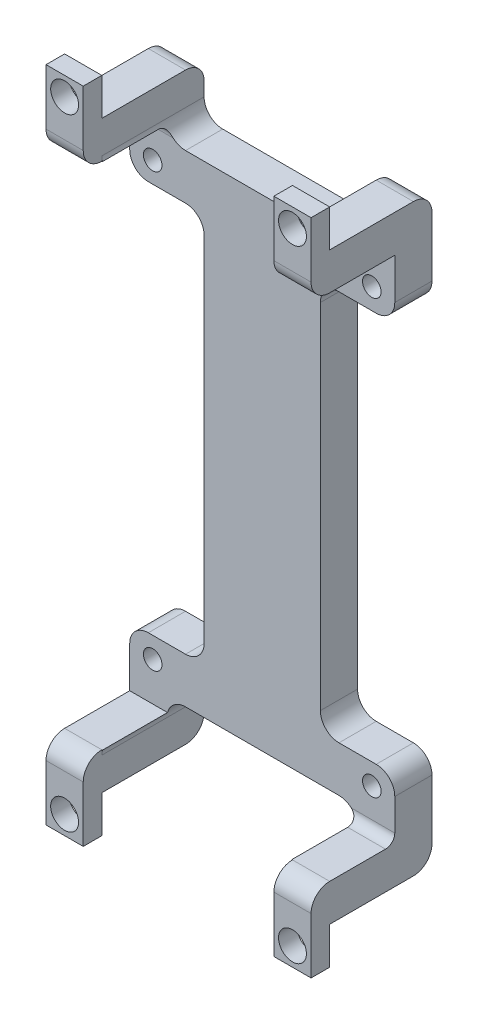
SolidWorks part; units mm, degrees
ref_plane "Front Plane" through (0, 0, 0) normal (0, 0, 1) x (1, 0, 0)
ref_plane "Top Plane" through (0, 0, 0) normal (0, 1, 0) x (1, 0, 0)
ref_plane "Right Plane" through (0, 0, 0) normal (1, 0, 0) x (0, 0, -1)
sketch "Sketch3" plane through (0, 0, 0) normal (0, 0, 1) x (-1, 0, 0)
  line L6 (-14.25, -25.9) -> (14.25, -25.9)
  line L7 (-14.25, -25.9) -> (-14.25, 25.9)
  line L8 (-14.25, 25.9) -> (14.25, 25.9)
  line L9 (14.25, -25.9) -> (14.25, 25.9)
  line L10 (-14.25, -25.9) -> (14.25, 25.9) construction
  line L11 (-14.25, 25.9) -> (14.25, -25.9) construction
  point P0 (0, 0)
  dimension "D1" = 51.8
  dimension "D2" = 28.5
extrude "Boss-Extrude4" add sketch "Sketch3" along normal blind 4
sketch "Sketch7" plane through (0, 25.9, 0) normal (0, 1, 0) x (1, 0, 0)
  line L1 (-14.25, -4) -> (-10.25, -4)
  line L2 (-14.25, -4) -> (-14.25, 0)
  line L3 (-14.25, 0) -> (-10.25, 0)
  line L4 (-10.25, -4) -> (-10.25, 0)
  line L5 (14.25, 0) -> (-14.25, 0) construction
  line L7 (14.25, -4) -> (10.25, -4)
  line L8 (14.25, -4) -> (14.25, 0)
  line L9 (14.25, 0) -> (10.25, 0)
  line L10 (10.25, -4) -> (10.25, 0)
  dimension "D1" = 4
  dimension "D2" = 4
extrude "Boss-Extrude5" add sketch "Sketch7" along normal blind 5.5
mirror "Mirror1" about plane through (0, 0, 0) normal (0, 1, 0) of "Boss-Extrude5"
sketch "Sketch8" plane through (0, 0, 4) normal (0, 0, 1) x (1, 0, 0)
  line L0 (14.25, -31.4) -> (14.25, 31.4) construction
  line L1 (-14.25, 31.4) -> (-10.25, 31.4)
  line L2 (-14.25, 31.4) -> (-14.25, 27.4)
  line L3 (-14.25, 27.4) -> (-10.25, 27.4)
  line L4 (-10.25, 31.4) -> (-10.25, 27.4)
  line L5 (10.25, 31.4) -> (14.25, 31.4)
  line L6 (10.25, 31.4) -> (10.25, 27.4)
  line L7 (10.25, 27.4) -> (14.25, 27.4)
  line L8 (14.25, 31.4) -> (14.25, 27.4)
  line L9 (0, 0) -> (-6.3978, 0) construction
  line L10 (14.25, -31.4) -> (14.25, -27.4)
  line L11 (10.25, -27.4) -> (14.25, -27.4)
  line L12 (10.25, -31.4) -> (10.25, -27.4)
  line L13 (10.25, -31.4) -> (14.25, -31.4)
  line L14 (-10.25, -31.4) -> (-10.25, -27.4)
  line L15 (-14.25, -27.4) -> (-10.25, -27.4)
  line L16 (-14.25, -31.4) -> (-14.25, -27.4)
  line L17 (-14.25, -31.4) -> (-10.25, -31.4)
  dimension "D1" = 4
extrude "Boss-Extrude6" add sketch "Sketch8" along normal blind 7
sketch "Sketch9" plane through (0, 0, 11) normal (0, 0, 1) x (1, 0, 0)
  line L9 (0, 0) -> (0, 10.6615) construction
  line L10 (-14.25, 27.4) -> (-10.25, 27.4)
  line L11 (-14.25, 27.4) -> (-14.25, 35.4)
  line L12 (-14.25, 35.4) -> (-10.25, 35.4)
  line L13 (-10.25, 27.4) -> (-10.25, 35.4)
  line L14 (8.4868, 0) -> (-8.4868, 0) construction
  line L15 (10.25, 27.4) -> (10.25, 35.4)
  line L16 (14.25, 35.4) -> (10.25, 35.4)
  line L17 (14.25, 27.4) -> (14.25, 35.4)
  line L18 (14.25, 27.4) -> (10.25, 27.4)
  line L19 (14.25, -27.4) -> (10.25, -27.4)
  line L20 (14.25, -27.4) -> (14.25, -35.4)
  line L21 (14.25, -35.4) -> (10.25, -35.4)
  line L22 (10.25, -27.4) -> (10.25, -35.4)
  line L23 (-10.25, -27.4) -> (-10.25, -35.4)
  line L24 (-14.25, -35.4) -> (-10.25, -35.4)
  line L25 (-14.25, -27.4) -> (-14.25, -35.4)
  line L26 (-14.25, -27.4) -> (-10.25, -27.4)
  line L27 (-14.25, 31.4) -> (-10.25, 31.4) construction
  line L28 (-12.25, 31.4) -> (-12.25, 35.4) construction
  line L29 (-12.25, 35.4) -> (-12.25, 31.4) construction
  circle A4 centre (-12.25, 33.4) radius 1.5
  circle A5 centre (12.25, 33.4) radius 1.5
  circle A6 centre (12.25, -33.4) radius 1.5
  circle A7 centre (-12.25, -33.4) radius 1.5
  dimension "D1" = 8
  dimension "D3" = 3
  dimension "D2" = 4
  dimension "D4" = 24.5
  dimension "D5" = 66.8
sketch "Sketch10" plane through (0, 0, 4) normal (0, 0, 1) x (1, 0, 0)
  line L0 (0, 0) -> (0, 13.006) construction
  line L1 (-8.3339, 0) -> (0, 0) construction
  circle A0 centre (-11.78, 23.25) radius 1
  circle A1 centre (-11.78, -23.25) radius 1
  circle A2 centre (11.78, -23.25) radius 1
  circle A3 centre (11.78, 23.25) radius 1
  dimension "D1" = 2
  dimension "D2" = 11.78
  dimension "D3" = 23.25
extrude "Cut-Extrude2" cut sketch "Sketch10" against normal blind 4
sketch "Sketch11" plane through (0, 0, 4) normal (0, 0, 1) x (1, 0, 0)
  line L0 (-14.25, 27.4) -> (-14.25, -27.4) construction
  line L1 (-14.25, 21) -> (-6.25, 21)
  line L2 (-14.25, 21) -> (-14.25, -21)
  line L3 (-14.25, -21) -> (-6.25, -21)
  line L4 (-6.25, 21) -> (-6.25, -21)
  line L5 (0, 0) -> (0, 8.8811) construction
  line L6 (6.25, 21) -> (6.25, -21)
  line L7 (14.25, -21) -> (6.25, -21)
  line L8 (14.25, 21) -> (14.25, -21)
  line L9 (14.25, 21) -> (6.25, 21)
  line L12 (10.25, 25.9) -> (-10.25, 25.9) construction
  dimension "D1" = 42
  dimension "D2" = 8
  dimension "D3" = 4.9
extrude "Cut-Extrude3" cut sketch "Sketch11" against normal through all
fillet "Fillet2" radius 1 2 edges at (12.25, -27.4, 4) (-12.25, 27.4, 4)
fillet "Fillet3" radius 2 4 edges at (-10.25, -25.9, 2) (10.25, -25.9, 2) (-10.25, 25.9, 2) (10.25, 25.9, 2)
extrude "Boss-Extrude8" add sketch "Sketch9" along normal blind 2
fillet "Fillet4" radius 2 20 edges at (-14.25, -21, 2) (-14.25, 21, 2) (-6.25, 21, 2) (-6.25, -21, 2) (6.25, 21, 2) (14.25, 21, 2) (14.25, -21, 2) (6.25, -21, 2) (-12.25, 31.4, 0) (-12.25, -27.4, 13) (-10.25, -27.4, 12) (12.25, 31.4, 0) (12.25, -27.4, 13) (10.25, -27.4, 12) (12.25, 27.4, 13) (10.25, 27.4, 12) (-12.25, 27.4, 13) (-10.25, 27.4, 12) (-12.25, -31.4, 0) (12.25, -31.4, 0)
